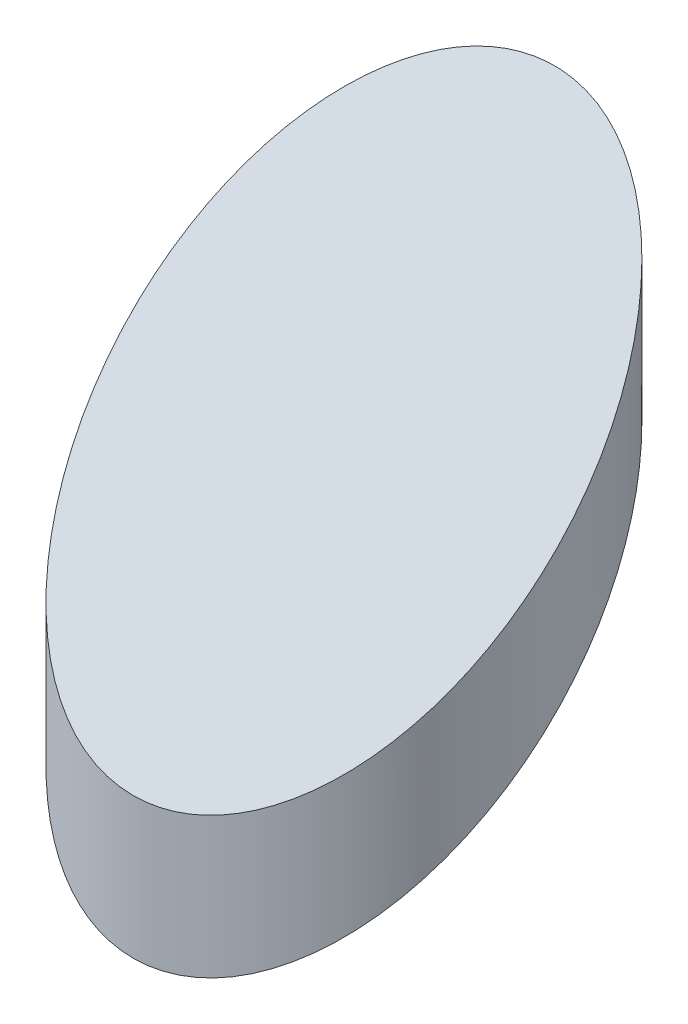
SolidWorks part; units mm, degrees
material "Glass"
ref_plane "Front Plane" through (0, 0, 0) normal (0, 0, 1) x (1, 0, 0)
ref_plane "Top Plane" through (0, 0, 0) normal (0, 1, 0) x (1, 0, 0)
ref_plane "Right Plane" through (0, 0, 0) normal (1, 0, 0) x (0, 0, -1)
sketch "Sketch2" plane through (0, 0, 0) normal (0, 1, 0) x (1, 0, 0)
  circle A0 centre (0, 0) radius 28.575
  dimension "D1" = 57.15
extrude "Boss-Extrude1" add sketch "Sketch2" along normal blind 80
sketch "Sketch3" plane through (0, 0, 0) normal (1, 0, 0) x (0, 0, -1)
  line L0 (28.575, 80) -> (-28.575, 80)
  line L1 (-28.575, 80) -> (-28.575, 19.11)
  line L2 (-28.575, 80) -> (-28.575, 0) construction
  line L3 (-28.575, 19.11) -> (28.575, 76.26)
  line L4 (28.575, 0) -> (28.575, 80) construction
  line L5 (28.575, 76.26) -> (28.575, 80)
  line L6 (28.575, 0) -> (28.575, 57.15)
  line L7 (28.575, 57.15) -> (-28.575, 0)
  line L8 (-28.575, 0) -> (28.575, 0)
  dimension "D1" = 45
  dimension "D2" = 13.5128
extrude "Cut-Extrude2" cut sketch "Sketch3" against normal through all both and the other way through all
